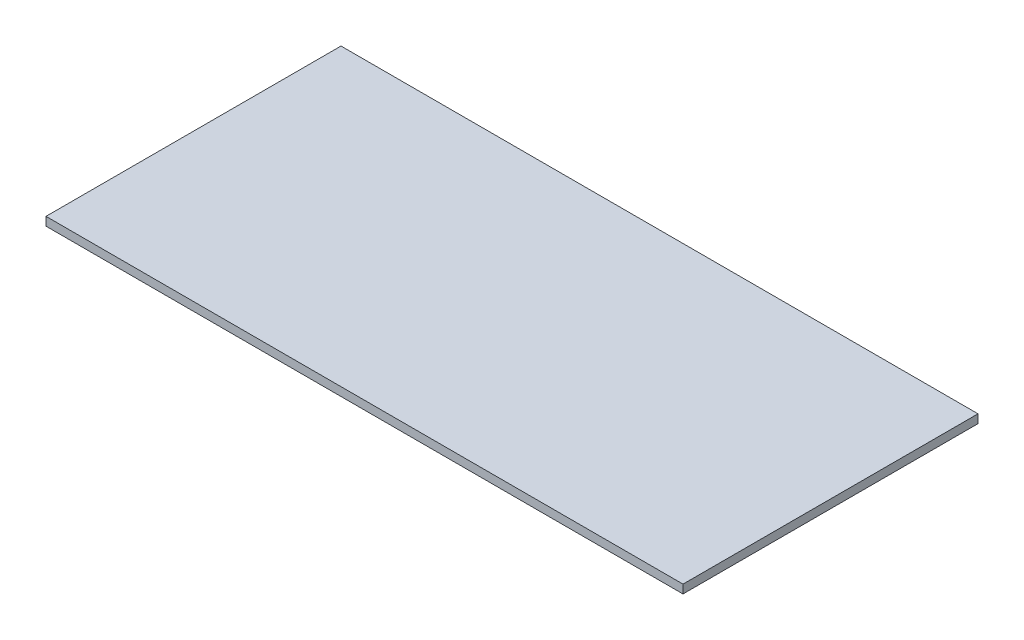
SolidWorks part; units mm, degrees
material "Acrylic (Medium-high impact)"
ref_plane "Front Plane" through (0, 0, 0) normal (0, 0, 1) x (1, 0, 0)
ref_plane "Top Plane" through (0, 0, 0) normal (0, 1, 0) x (1, 0, 0)
ref_plane "Right Plane" through (0, 0, 0) normal (1, 0, 0) x (0, 0, -1)
sketch "Sketch1" plane through (0, 0, 0) normal (0, 1, 0) x (1, 0, 0)
  line L1 (-94.615, -43.815) -> (94.615, -43.815)
  line L2 (-94.615, -43.815) -> (-94.615, 43.815)
  line L3 (-94.615, 43.815) -> (94.615, 43.815)
  line L4 (94.615, -43.815) -> (94.615, 43.815)
  line L5 (-94.615, -43.815) -> (94.615, 43.815) construction
  line L6 (-94.615, 43.815) -> (94.615, -43.815) construction
  point P0 (0, 0)
  dimension "D1" = 87.63
  dimension "D2" = 189.23
extrude "Boss-Extrude1" add sketch "Sketch1" along normal blind 2.54
